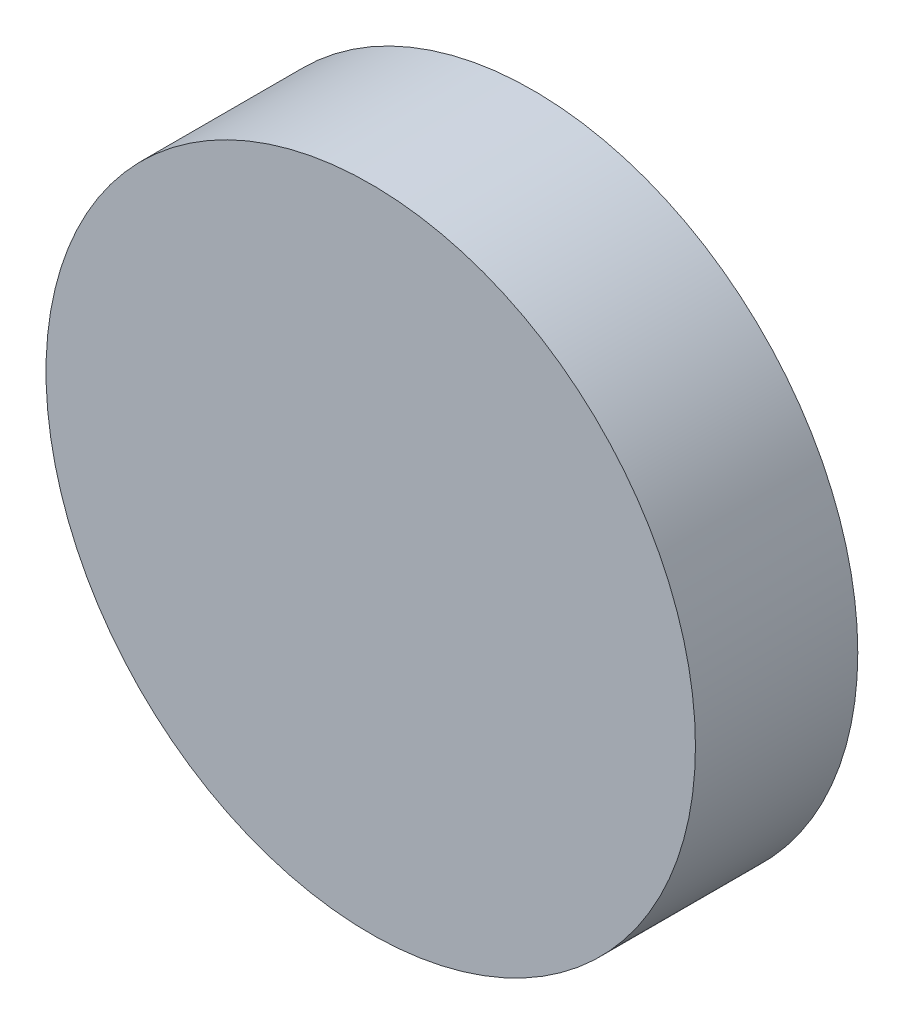
SolidWorks part; units mm, degrees
ref_plane "Front Plane" through (0, 0, 0) normal (0, 0, 1) x (1, 0, 0)
ref_plane "Top Plane" through (0, 0, 0) normal (0, 1, 0) x (1, 0, 0)
ref_plane "Right Plane" through (0, 0, 0) normal (1, 0, 0) x (0, 0, -1)
sketch "Sketch2" plane through (0, 0, 0) normal (0, 0, 1) x (1, 0, 0)
  circle A0 centre (0, 0) radius 2
  dimension "D1" = 4
extrude "Boss-Extrude1" add sketch "Sketch2" along normal blind 1
